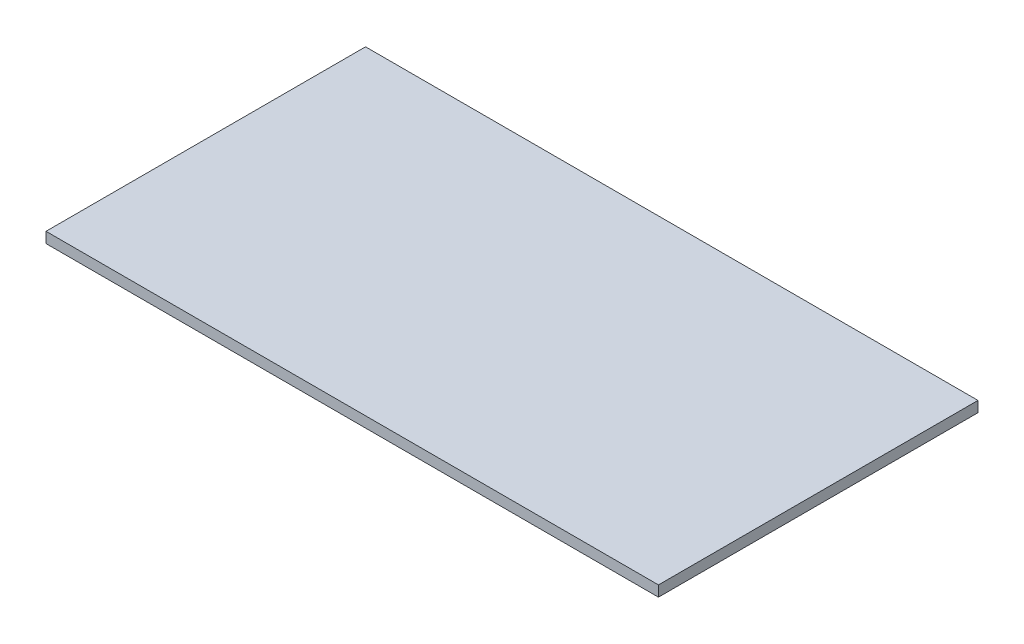
SolidWorks part; units mm, degrees
material "Pine"
ref_plane "Front Plane" through (0, 0, 0) normal (0, 0, 1) x (1, 0, 0)
ref_plane "Top Plane" through (0, 0, 0) normal (0, 1, 0) x (1, 0, 0)
ref_plane "Right Plane" through (0, 0, 0) normal (1, 0, 0) x (0, 0, -1)
sketch "Sketch1" plane through (0, 0, 0) normal (0, 1, 0) x (1, 0, 0)
  line L1 (-575, 300) -> (575, 300)
  line L2 (-575, 300) -> (-575, -300)
  line L3 (-575, -300) -> (575, -300)
  line L4 (575, 300) -> (575, -300)
  line L5 (-575, 300) -> (575, -300) construction
  line L6 (-575, -300) -> (575, 300) construction
  point P0 (0, 0)
  dimension "D1" = 1150
  dimension "D2" = 600
extrude "Boss-Extrude1" add sketch "Sketch1" along normal blind 20
